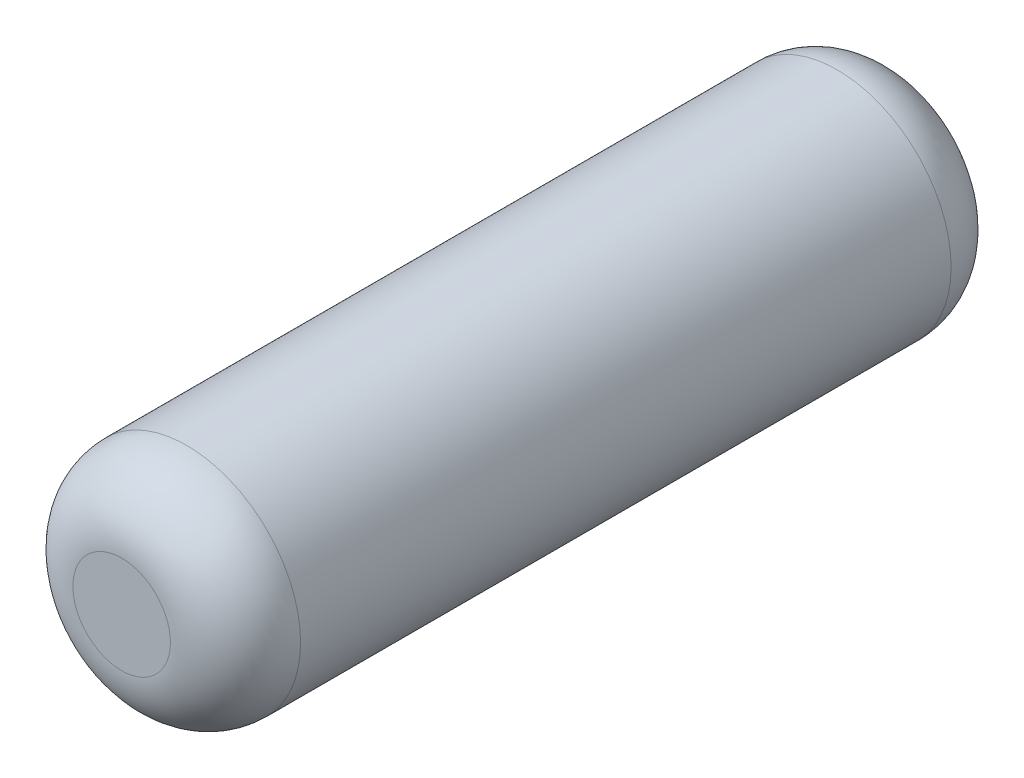
SolidWorks part; units mm, degrees
ref_plane "Front Plane" through (0, 0, 0) normal (0, 0, 1) x (1, 0, 0)
ref_plane "Top Plane" through (0, 0, 0) normal (0, 1, 0) x (1, 0, 0)
ref_plane "Right Plane" through (0, 0, 0) normal (1, 0, 0) x (0, 0, -1)
sketch "Sketch2" plane through (0, 0, 0) normal (0, 0, 1) x (1, 0, 0)
  circle A0 centre (0, 0) radius 44.45
  dimension "D1" = 88.9
extrude "Boss-Extrude1" add sketch "Sketch2" along normal blind 304.8
fillet "Fillet2" radius 25.4 2 edges at (44.45, 0, 304.8) (44.45, 0, 0)
sketch "Sketch3" plane through (0, 0, 0) normal (0, 0, -1) x (-1, 0, 0)
  point P0 (0, 0)
ref_plane "Plane1" through (0, 0, 279.4) normal (0, 0, 1) x (1, 0, 0)
sketch "Sketch4" plane through (0, 0, 279.4) normal (0, 0, 1) x (1, 0, 0)
  point P0 (0, 0)
sketch3d "3DSketch1"
  line L0 (0, 0, 279.4) -> (0, 0, 0)
